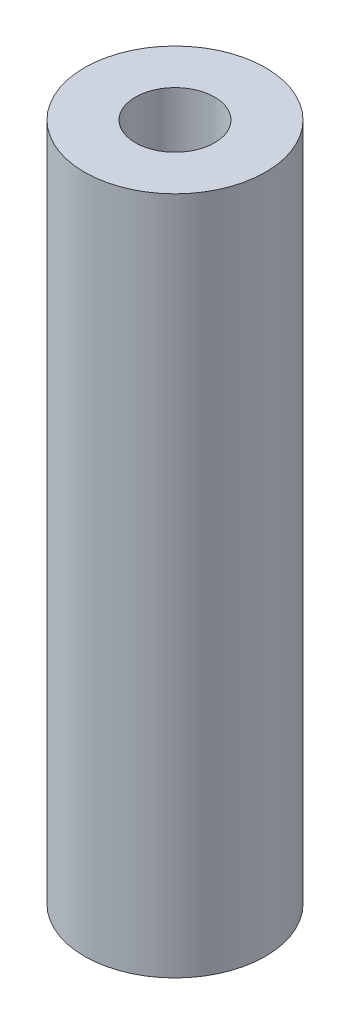
SolidWorks part; units mm, degrees
ref_plane "前视基准面" through (0, 0, 0) normal (0, 0, 1) x (1, 0, 0)
ref_plane "上视基准面" through (0, 0, 0) normal (0, 1, 0) x (1, 0, 0)
ref_plane "右视基准面" through (0, 0, 0) normal (1, 0, 0) x (0, 0, -1)
sketch "草图1" plane through (0, 0, 0) normal (0, 1, 0) x (1, 0, 0)
  circle A0 centre (-0.7951, 0.385) radius 4
  circle A1 centre (-0.7951, 0.385) radius 1.75
  dimension "D1" = 3.5
  dimension "D2" = 8
extrude "凸台-拉伸1" add sketch "草图1" along normal blind 30
